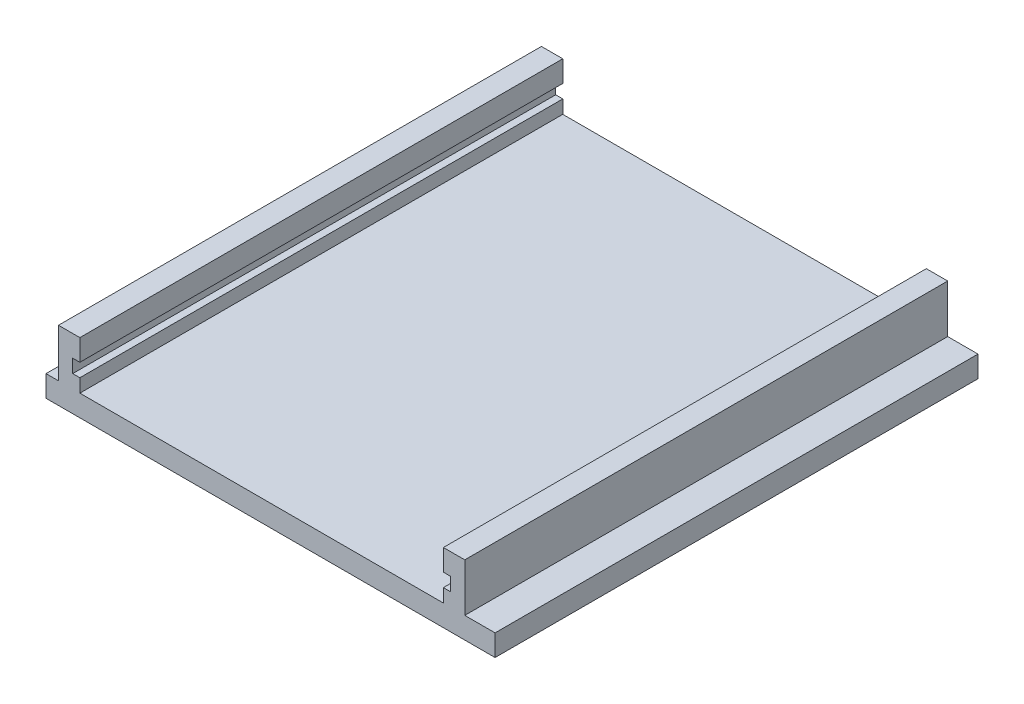
SolidWorks part; units mm, degrees
ref_plane "Front Plane" through (0, 0, 0) normal (0, 0, 1) x (1, 0, 0)
ref_plane "Top Plane" through (0, 0, 0) normal (0, 1, 0) x (1, 0, 0)
ref_plane "Right Plane" through (0, 0, 0) normal (1, 0, 0) x (0, 0, -1)
sketch "Sketch1" plane through (0, 0, 0) normal (0, 1, 0) x (1, 0, 0)
  line L1 (0, 0) -> (64.008, 0)
  line L2 (0, 0) -> (0, 68.834)
  line L3 (0, 68.834) -> (64.008, 68.834)
  line L4 (64.008, 0) -> (64.008, 68.834)
extrude "Boss-Extrude1" add sketch "Sketch1" along normal blind 3.048
sketch "Sketch2" plane through (0, 3.048, 0) normal (0, 1, 0) x (1, 0, 0)
  line L0 (64.008, 68.834) -> (0, 68.834) construction
  line L1 (59.69, 68.834) -> (56.642, 68.834)
  line L2 (59.69, 68.834) -> (59.69, 0)
  line L3 (59.69, 0) -> (56.642, 0)
  line L4 (56.642, 68.834) -> (56.642, 0)
  line L5 (0, 0) -> (64.008, 0) construction
  point P8 (0, 0)
  point P9 (0, 0)
  point P10 (0, 0)
extrude "Boss-Extrude2" add sketch "Sketch2" along normal blind 6.858
sketch "Sketch3" plane through (0, 0, 0) normal (0, 0, 1) x (1, 0, 0)
  line L0 (56.642, 9.906) -> (56.642, 3.048) construction
  line L1 (56.642, 6.858) -> (57.658, 6.858)
  line L2 (56.642, 6.858) -> (56.642, 4.953)
  line L3 (56.642, 4.953) -> (57.658, 4.953)
  line L4 (57.658, 6.858) -> (57.658, 4.953)
  point P6 (0, 0)
  point P7 (0, 0)
  point P8 (0, 0)
  point P10 (0, 0)
extrude "Cut-Extrude1" cut sketch "Sketch3" against normal through all
sketch "Sketch4" plane through (0, 3.048, 0) normal (0, 1, 0) x (1, 0, 0)
  line L0 (0, 0) -> (56.642, 0) construction
  line L1 (4.826, 0) -> (1.778, 0)
  line L2 (4.826, 0) -> (4.826, 68.834)
  line L3 (4.826, 68.834) -> (1.778, 68.834)
  line L4 (1.778, 0) -> (1.778, 68.834)
  line L5 (56.642, 68.834) -> (0, 68.834) construction
  point P8 (0, 0)
  point P9 (0, 0)
  point P10 (0, 0)
extrude "Boss-Extrude3" add sketch "Sketch4" along normal blind 6.858
sketch "Sketch5" plane through (0, 0, 0) normal (0, 0, 1) x (1, 0, 0)
  line L1 (4.826, 6.858) -> (3.81, 6.858)
  line L2 (4.826, 6.858) -> (4.826, 4.953)
  line L3 (4.826, 4.953) -> (3.81, 4.953)
  line L4 (3.81, 6.858) -> (3.81, 4.953)
  line L5 (4.826, 9.906) -> (4.826, 3.048) construction
  point P4 (0, 0)
  point P5 (4.826, 7.0517)
  point P6 (0, 0)
  point P7 (0, 0)
  point P10 (0, 0)
extrude "Cut-Extrude2" cut sketch "Sketch5" against normal through all
